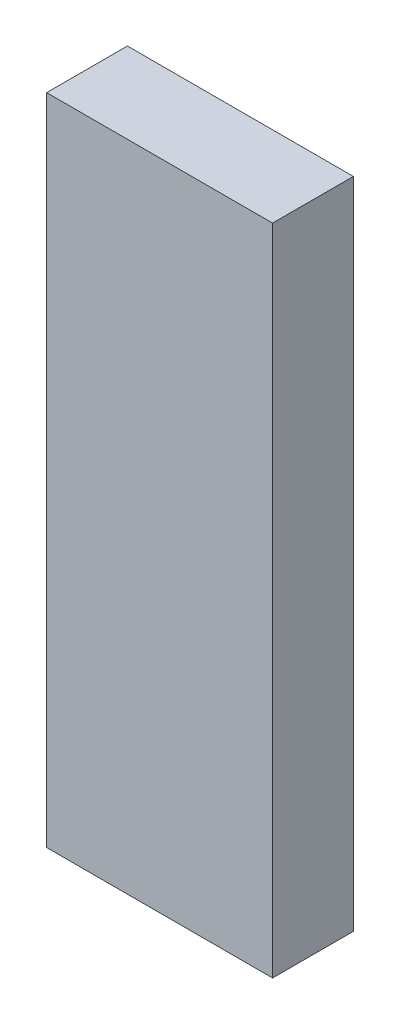
SolidWorks part; units mm, degrees
ref_plane "Спереди" through (0, 0, 0) normal (0, 0, 1) x (1, 0, 0)
ref_plane "Сверху" through (0, 0, 0) normal (0, 1, 0) x (1, 0, 0)
ref_plane "Справа" through (0, 0, 0) normal (1, 0, 0) x (0, 0, -1)
sketch "Эскиз1" plane through (0, 0, 0) normal (0, 0, 1) x (1, 0, 0)
  line L1 (-447.5, 1295) -> (447.5, 1295)
  line L2 (-447.5, 1295) -> (-447.5, -1295)
  line L3 (-447.5, -1295) -> (447.5, -1295)
  line L4 (447.5, 1295) -> (447.5, -1295)
  line L5 (-447.5, 1295) -> (447.5, -1295) construction
  line L6 (-447.5, -1295) -> (447.5, 1295) construction
  point P0 (0, 0)
extrude "Бобышка-Вытянуть1" add sketch "Эскиз1" along normal blind 320
sketch "Эскиз2" plane through (0, 0, 320) normal (0, 0, 1) x (1, 0, 0)
  circle A0 centre (290.5446, 0) radius 44.5726
  text T0 "ПК" font "Arial" height 300
